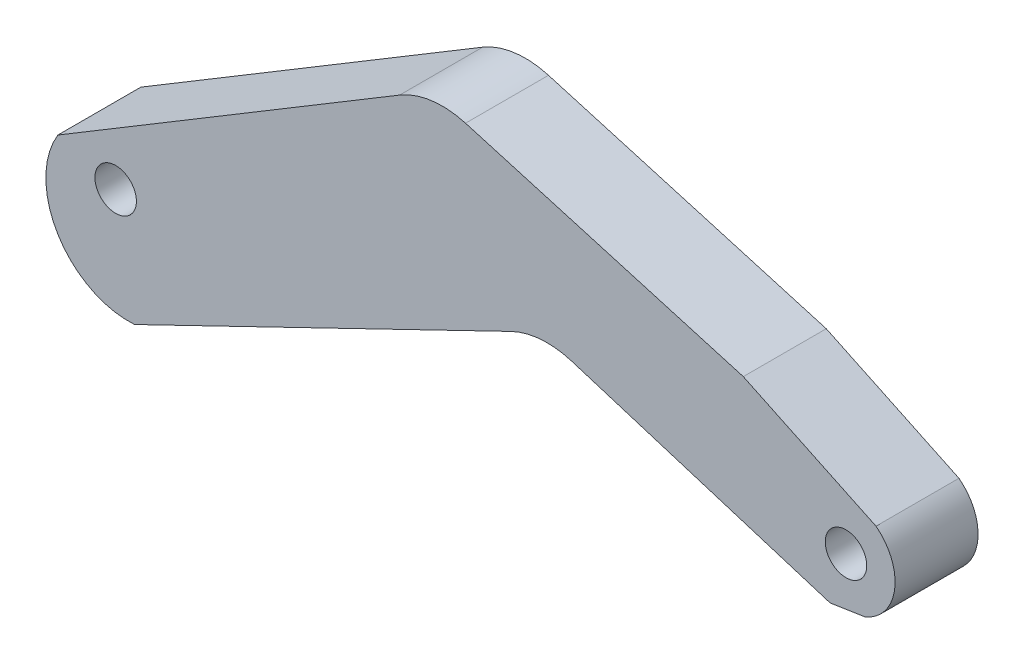
SolidWorks part; units mm, degrees
ref_plane "Front Plane" through (0, 0, 0) normal (0, 0, 1) x (1, 0, 0)
ref_plane "Top Plane" through (0, 0, 0) normal (0, 1, 0) x (1, 0, 0)
ref_plane "Right Plane" through (0, 0, 0) normal (1, 0, 0) x (0, 0, -1)
sketch "Sketch1" plane through (0, 0, 0) normal (0, 0, 1) x (1, 0, 0)
  line L1 (19.8269, 2.0082) -> (13.4285, 5.0528)
  line L2 (17.6114, -2.3037) -> (19.3233, -2.0404)
  line L4 (17.6114, -2.3037) -> (5.1566, 1.5597)
  line L8 (2.2286, 1.3396) -> (-15.9228, -7.4477)
  line L9 (-3.1389, 8.525) -> (-19.6187, -1.3836)
  line L10 (-19.6187, -1.3836) -> (-3.1389, 8.525)
  line L11 (0.0369, 8.9385) -> (13.4285, 5.0528)
  arc A1 (19.3233, -2.0404) -> (19.8269, 2.0082) centre (18.3809, 0.1325) ccw
  circle A2 centre (18.3809, 0.1325) radius 1
  circle A3 centre (-16.8329, -2.2607) radius 1
  arc A4 (0.0369, 8.9385) -> (-3.1389, 8.525) centre (-1.0778, 5.0969) ccw
  arc A5 (-19.6187, -1.3836) -> (-15.9228, -7.4477) centre (-16.1981, -3.4572) ccw
  arc A6 (5.1566, 1.5597) -> (2.2286, 1.3396) centre (3.9715, -2.2607) ccw
  point P3 (2.1053, 0)
  dimension "D2" = 4
  dimension "D3" = 2
  dimension "D4" = 4
  dimension "D1" = 4
extrude "Boss-Extrude1" add sketch "Sketch1" along normal blind 4 contours A6 L4 L2 A1 L1 L11 A4 L9 A5 L8 A3 A2
